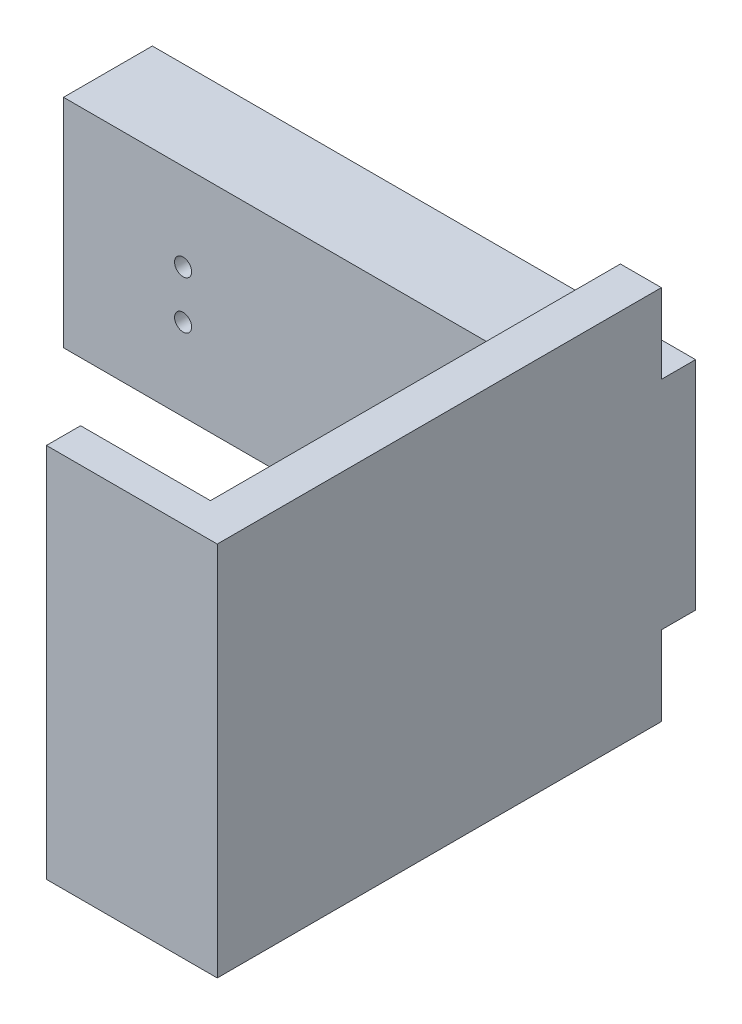
SolidWorks part; units mm, degrees
ref_plane "Front Plane" through (0, 0, 0) normal (0, 0, 1) x (1, 0, 0)
ref_plane "Top Plane" through (0, 0, 0) normal (0, 1, 0) x (1, 0, 0)
ref_plane "Right Plane" through (0, 0, 0) normal (1, 0, 0) x (0, 0, -1)
sketch "Sketch1" plane through (0, 0, 0) normal (0, 0, 1) x (1, 0, 0)
  line L1 (0, 0) -> (-50, 0)
  line L2 (0, 0) -> (0, 110)
  line L3 (0, 110) -> (-50, 110)
  line L4 (-50, 0) -> (-50, 110)
  dimension "D1" = 50
  dimension "D2" = 110
extrude "Boss-Extrude1" add sketch "Sketch1" along normal blind 10
sketch "Sketch2" plane through (0, 0, 0) normal (0, 0, -1) x (-1, 0, 0)
  line L0 (50, 0) -> (0, 0) construction
  line L1 (0, 110) -> (12, 110)
  line L2 (0, 110) -> (0, 0)
  line L3 (0, 0) -> (12, 0)
  line L4 (12, 110) -> (12, 0)
  dimension "D1" = 12
extrude "Boss-Extrude2" add sketch "Sketch2" along normal blind 120
sketch "Sketch3" plane through (-12, 0, 0) normal (-1, 0, 0) x (0, 0, 1)
  line L0 (-120, 0) -> (-120, 110) construction
  line L1 (-120, 76.75) -> (-114, 76.75)
  line L2 (-120, 76.75) -> (-120, 33.25)
  line L3 (-120, 33.25) -> (-114, 33.25)
  line L4 (-114, 76.75) -> (-114, 33.25)
  line L5 (-120, 0) -> (0, 0) construction
  line L6 (-120, 23.25) -> (-104, 23.25)
  line L7 (-104, 23.25) -> (-104, 86.75)
  line L8 (-104, 86.75) -> (-120, 86.75)
  line M5 (-120, 110) -> (-120, 0)
  dimension "D1" = 43.5
  dimension "D2" = 33.25
  dimension "D3" = 10
  dimension "D4" = 10
  dimension "D5" = 16
  dimension "D6" = 10
extrude "Boss-Extrude4" add sketch "Sketch3" along normal blind 152 contours L7 L8 L1 L4 L3 L6 M5
sketch "Sketch4" plane through (0, 0, -120) normal (0, 0, -1) x (-1, 0, 0)
  line L0 (12, 86.75) -> (0, 86.75)
  line L1 (164, 86.75) -> (12, 86.75)
  line L2 (164, 86.75) -> (164, 76.75)
  line L3 (164, 76.75) -> (12, 76.75)
  line L5 (164, 33.25) -> (12, 33.25)
  line L6 (164, 33.25) -> (164, 23.25)
  line L7 (164, 23.25) -> (12, 23.25)
  line L9 (0, 110) -> (0, 0) construction
  line L10 (0, 86.75) -> (0, 23.25)
  line L11 (0, 23.25) -> (12, 23.25)
  line L12 (12, 76.75) -> (12, 33.25)
extrude "Boss-Extrude5" add sketch "Sketch4" along normal blind 10
sketch "Sketch5" plane through (0, 76.75, 0) normal (0, -1, 0) x (1, 0, 0)
  line L0 (-164, -130) -> (-164, -114) construction
  line L1 (-12, -130) -> (-164, -130)
  line L2 (-12, -130) -> (-12, -122)
  line L3 (-12, -122) -> (-164, -122)
  line L4 (-164, -130) -> (-164, -122)
  dimension "D1" = 8
extrude "Boss-Extrude6" add sketch "Sketch5" along normal blind 10
sketch "Sketch6" plane through (0, 33.25, 0) normal (0, 1, 0) x (1, 0, 0)
  line L0 (-164, 130) -> (-164, 114) construction
  line L1 (-12, 130) -> (-164, 130)
  line L2 (-12, 130) -> (-12, 122)
  line L3 (-12, 122) -> (-164, 122)
  line L4 (-164, 130) -> (-164, 122)
  dimension "D1" = 8
extrude "Boss-Extrude7" add sketch "Sketch6" along normal blind 10
sketch "Sketch7" plane through (0, 0, -104) normal (0, 0, 1) x (1, 0, 0)
  line L0 (-164, 86.75) -> (-12, 86.75) construction
  line L2 (-164, 23.25) -> (-164, 86.75) construction
  circle A0 centre (-124, 61.25) radius 2.5
  circle A1 centre (-124, 47.25) radius 2.5
  dimension "D1" = 5
  dimension "D2" = 5
  dimension "D6" = 40
  dimension "D3" = 14
  dimension "D4" = 25.5
  dimension "D5" = 40
extrude "Cut-Extrude1" cut sketch "Sketch7" against normal blind 87
sketch "Sketch8" plane through (-164, 0, 0) normal (-1, 0, 0) x (0, 0, 1)
  line L1 (-104, 86.75) -> (-130, 86.75)
  line L2 (-104, 86.75) -> (-104, 23.25)
  line L3 (-104, 23.25) -> (-130, 23.25)
  line L4 (-130, 86.75) -> (-130, 23.25)
extrude "Cut-Extrude2" cut sketch "Sketch8" against normal blind 5
